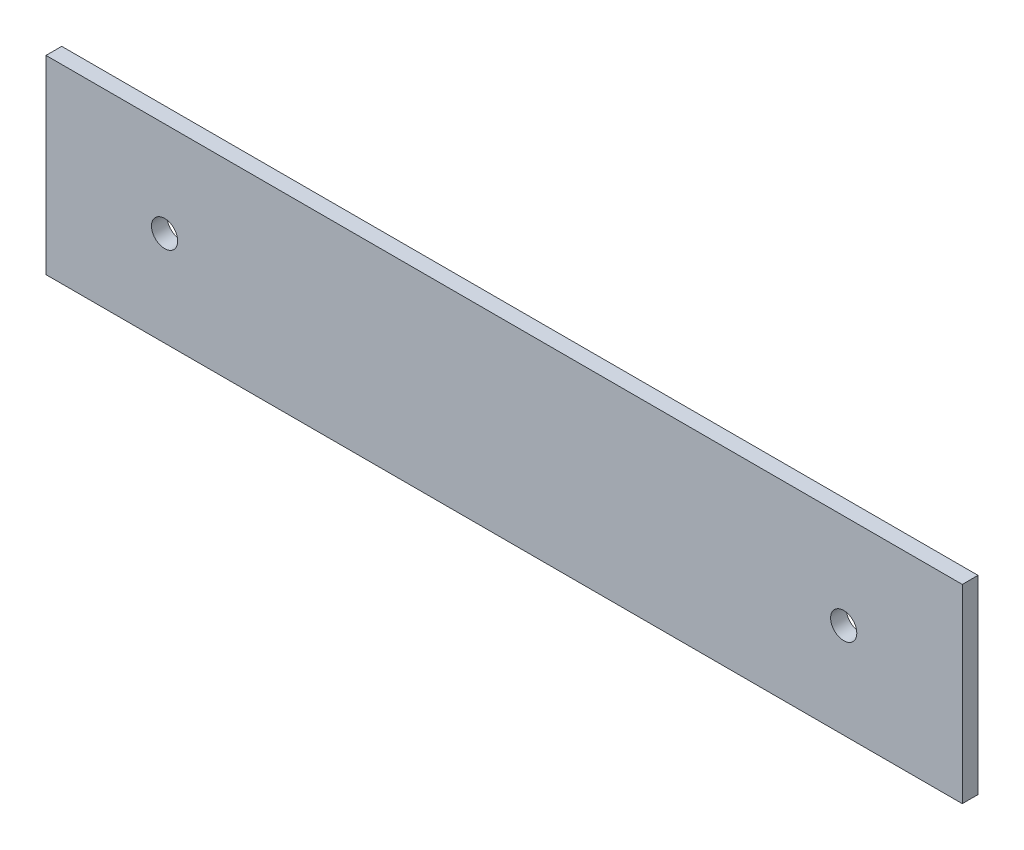
SolidWorks part; units mm, degrees
material "Custom Plastic"
ref_plane "Plan de face" through (0, 0, 0) normal (0, 0, 1) x (1, 0, 0)
ref_plane "Plan de dessus" through (0, 0, 0) normal (0, 1, 0) x (1, 0, 0)
ref_plane "Plan de droite" through (0, 0, 0) normal (1, 0, 0) x (0, 0, -1)
sketch "Esquisse2" plane through (0, 0, 0) normal (0, 1, 0) x (1, 0, 0)
  line L0 (-76.2817, -46.3798) -> (-76.2817, -1.166) construction
  line L1 (-76.2817, -1.166) -> (98.7183, -1.166)
  line L2 (-76.2817, -1.166) -> (-76.2817, -4.166)
  line L3 (-76.2817, -4.166) -> (98.7183, -4.166)
  line L4 (98.7183, -1.166) -> (98.7183, -4.166)
  line L5 (-76.2817, -1.166) -> (98.7183, -4.166) construction
  line L6 (-76.2817, -4.166) -> (98.7183, -1.166) construction
  line L14 (98.7183, -65.8798) -> (98.7183, -1.166) construction
  point P4 (11.2183, -2.666)
  dimension "D1" = 3
extrude "Boss.-Extru.1" add sketch "Esquisse2" along normal up to surface (36.27 mm away)
sketch "Esquisse3" plane through (0, 0, 4.166) normal (0, 0, 1) x (1, 0, 0)
  line L2 (-53.6317, 18.135) -> (76.0683, 18.135) construction
  line L3 (76.0683, 18.135) -> (98.7183, 18.135) construction
  line L4 (98.7183, 36.27) -> (98.7183, 0) construction
  line L5 (-53.6317, 18.135) -> (-76.2817, 18.135) construction
  line L6 (-76.2817, 36.27) -> (-76.2817, 0) construction
  circle A3 centre (-53.6317, 18.135) radius 2.5
  circle A5 centre (76.0683, 18.135) radius 2.5
  point P12 (11.2183, 18.135)
  dimension "D2" = 129.7
  dimension "D1" = 5
extrude "Enlèv. mat.-Extru.1" cut sketch "Esquisse3" against normal through all
